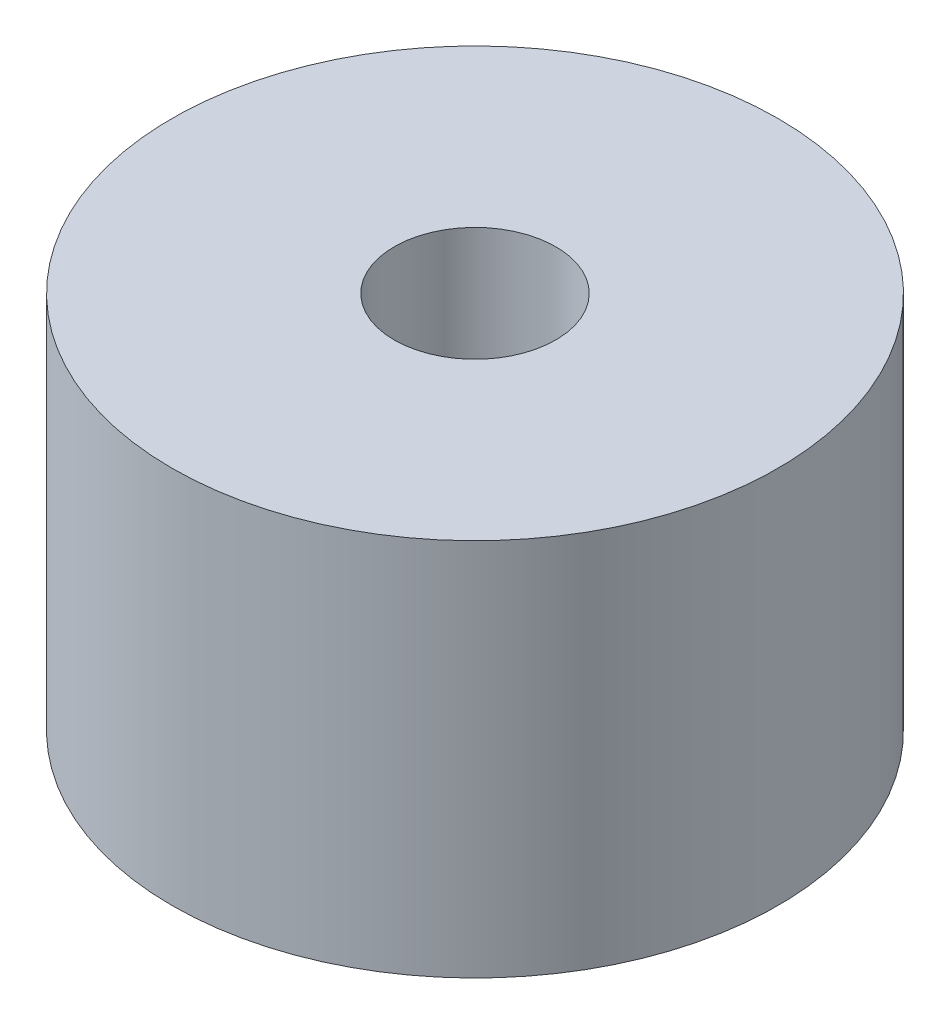
SolidWorks part; units mm, degrees
ref_plane "前视基准面" through (0, 0, 0) normal (0, 0, 1) x (1, 0, 0)
ref_plane "上视基准面" through (0, 0, 0) normal (0, 1, 0) x (1, 0, 0)
ref_plane "右视基准面" through (0, 0, 0) normal (1, 0, 0) x (0, 0, -1)
other "Configuration Table"
sketch "草图1" plane through (0, 0, 0) normal (0, 1, 0) x (1, 0, 0)
  circle A0 centre (0, 0) radius 1.6
  circle A1 centre (0, 0) radius 6
  dimension "D1" = 3.2
  dimension "D2" = 12
extrude "凸台-拉伸1" add sketch "草图1" along normal blind 7.5
